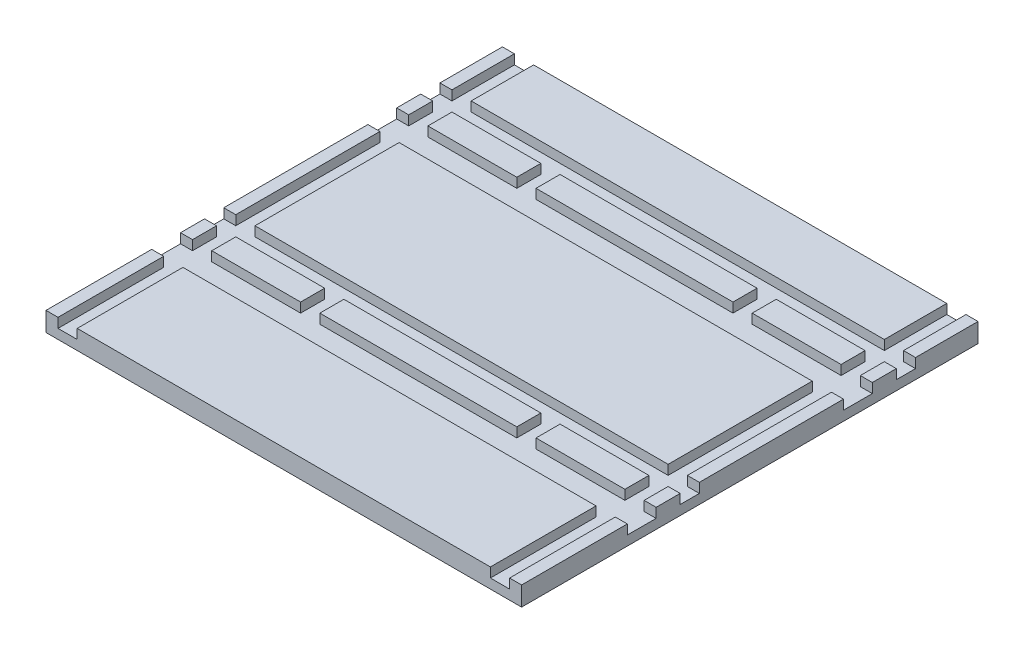
SolidWorks part; units mm, degrees
ref_plane "Front Plane" through (0, 0, 0) normal (0, 0, 1) x (1, 0, 0)
ref_plane "Top Plane" through (0, 0, 0) normal (0, 1, 0) x (1, 0, 0)
ref_plane "Right Plane" through (0, 0, 0) normal (1, 0, 0) x (0, 0, -1)
sketch "Sketch2" plane through (0, 0, 0) normal (0, 1, 0) x (1, 0, 0)
  line L9 (-60.325, -60.325) -> (60.325, -60.325)
  line L10 (-60.325, -60.325) -> (-60.325, 60.325)
  line L11 (-60.325, 60.325) -> (60.325, 60.325)
  line L16 (60.325, -60.325) -> (60.325, 60.325)
  line L17 (-60.325, -60.325) -> (60.325, 60.325) construction
  line L18 (-60.325, 60.325) -> (60.325, -60.325) construction
  point P0 (0, 0)
  dimension "D1" = 120.65
  dimension "D2" = 120.65
extrude "Boss-Extrude1" add sketch "Sketch2" along normal blind 2.54
sketch "Sketch3" plane through (0, 2.54, 0) normal (0, 1, 0) x (1, 0, 0)
  line L0 (57.15, 0) -> (-57.15, 0) construction
  line L5 (-57.15, -57.15) -> (57.15, 57.15) construction
  line L6 (-57.15, 57.15) -> (57.15, -57.15) construction
  line L7 (-57.15, 0) -> (0, 57.15) construction
  line L8 (0, 57.15) -> (0, -57.15) construction
  line L9 (0, -57.15) -> (57.15, 0) construction
  line L10 (57.15, 0) -> (0, 57.15) construction
  line L11 (0, -57.15) -> (-57.15, 0) construction
  line L12 (-60.325, -24.765) -> (-59.69, -24.765)
  line L13 (-60.325, 60.325) -> (-60.325, -60.325) construction
  line L14 (60.325, -60.325) -> (60.325, 60.325) construction
  line L15 (60.325, -32.385) -> (59.69, -32.385)
  line L16 (-28.575, -28.575) -> (28.575, -28.575) construction
  line L17 (-31.115, -24.765) -> (-31.115, -18.415)
  line L18 (-26.035, -24.765) -> (-26.035, -18.415)
  line L19 (-28.575, -28.575) -> (-28.575, 28.575) construction
  line L20 (28.575, 28.575) -> (28.575, -28.575) construction
  line L21 (-57.15, 57.15) -> (-57.15, -57.15) construction
  line L22 (-57.15, -57.15) -> (57.15, -57.15) construction
  line L23 (57.15, -57.15) -> (57.15, 57.15) construction
  line L24 (57.15, 57.15) -> (-57.15, 57.15) construction
  line L25 (-59.69, 60.325) -> (-59.69, 43.815)
  line L26 (60.325, 60.325) -> (-60.325, 60.325) construction
  line L27 (-60.325, -60.325) -> (60.325, -60.325) construction
  line L28 (-54.61, 60.325) -> (-54.61, 43.815)
  line L29 (-60.325, -15.875) -> (60.325, -15.875) construction
  line L30 (-60.325, -18.415) -> (-59.69, -18.415)
  line L31 (60.325, -13.335) -> (59.69, -13.335)
  line L32 (-26.035, -24.765) -> (26.035, -24.765)
  line L33 (-26.035, -18.415) -> (26.035, -18.415)
  line L34 (31.115, -24.765) -> (31.115, -18.415)
  line L35 (26.035, -24.765) -> (26.035, -18.415)
  line L36 (31.115, -24.765) -> (54.61, -24.765)
  line L37 (31.115, -18.415) -> (54.61, -18.415)
  line L38 (-59.69, -13.335) -> (-60.325, -13.335)
  line L39 (-54.61, -18.415) -> (-31.115, -18.415)
  line L40 (-54.61, -24.765) -> (-31.115, -24.765)
  line L41 (-59.69, -32.385) -> (-60.325, -32.385)
  line L42 (59.69, 60.325) -> (59.69, 43.815)
  line L43 (54.61, 60.325) -> (54.61, 43.815)
  line L44 (-54.61, -32.385) -> (-54.61, -60.325)
  line L45 (-54.61, -18.415) -> (-54.61, -24.765)
  line L46 (54.61, -32.385) -> (54.61, -60.325)
  line L47 (59.69, -24.765) -> (60.325, -24.765)
  line L48 (59.69, -18.415) -> (60.325, -18.415)
  line L49 (54.61, -18.415) -> (54.61, -24.765)
  line L50 (54.61, -13.335) -> (-54.61, -13.335)
  line L51 (54.61, -32.385) -> (-54.61, -32.385)
  line L52 (59.69, -32.385) -> (59.69, -60.325)
  line L53 (59.69, -18.415) -> (59.69, -24.765)
  line L54 (-59.69, -18.415) -> (-59.69, -24.765)
  line L55 (-59.69, -32.385) -> (-59.69, -60.325)
  line L56 (60.325, -60.325) -> (59.69, -60.325)
  line L57 (-60.325, -60.325) -> (-60.325, -32.385)
  line L58 (-60.325, 60.325) -> (-59.69, 60.325)
  line L59 (60.325, 60.325) -> (60.325, 43.815)
  line L60 (-59.69, -60.325) -> (-60.325, -60.325)
  line L61 (54.61, -60.325) -> (-54.61, -60.325)
  line L62 (60.325, -32.385) -> (60.325, -60.325)
  line L63 (60.325, -18.415) -> (60.325, -24.765)
  line L64 (-60.325, -13.335) -> (-60.325, 24.765)
  line L65 (-60.325, -24.765) -> (-60.325, -18.415)
  line L66 (-54.61, 32.385) -> (-31.115, 32.385)
  line L67 (54.61, 43.815) -> (-54.61, 43.815)
  line L68 (-26.035, 32.385) -> (26.035, 32.385)
  line L69 (26.035, 32.385) -> (26.035, 38.735)
  line L70 (-26.035, 32.385) -> (-26.035, 38.735)
  line L71 (31.115, 32.385) -> (54.61, 32.385)
  line L72 (-54.61, 38.735) -> (-31.115, 38.735)
  line L73 (-26.035, 38.735) -> (26.035, 38.735)
  line L74 (-54.61, 38.735) -> (-54.61, 32.385)
  line L75 (31.115, 32.385) -> (31.115, 38.735)
  line L76 (54.61, 24.765) -> (-54.61, 24.765)
  line L77 (-31.115, 32.385) -> (-31.115, 38.735)
  line L78 (31.115, 38.735) -> (54.61, 38.735)
  line L79 (54.61, 38.735) -> (54.61, 32.385)
  line L80 (-28.575, 28.575) -> (28.575, 28.575) construction
  line L81 (-54.61, 24.765) -> (-54.61, -13.335)
  line L82 (-54.61, 38.735) -> (-54.61, 32.385)
  line L83 (54.61, 38.735) -> (54.61, 32.385)
  line L84 (54.61, 24.765) -> (54.61, -13.335)
  line L85 (-54.61, 60.325) -> (54.61, 60.325)
  line L86 (59.69, 60.325) -> (60.325, 60.325)
  line L87 (-59.69, 24.765) -> (-60.325, 24.765)
  line L88 (-59.69, 32.385) -> (-60.325, 32.385)
  line L89 (-59.69, 38.735) -> (-60.325, 38.735)
  line L90 (-59.69, 43.815) -> (-60.325, 43.815)
  line L91 (-59.69, 38.735) -> (-59.69, 32.385)
  line L92 (-60.325, 43.815) -> (-60.325, 60.325)
  line L93 (-59.69, 24.765) -> (-59.69, -13.335)
  line L94 (-60.325, 32.385) -> (-60.325, 38.735)
  line L95 (59.69, 43.815) -> (60.325, 43.815)
  line L96 (59.69, 38.735) -> (60.325, 38.735)
  line L97 (59.69, 32.385) -> (60.325, 32.385)
  line L98 (59.69, 24.765) -> (60.325, 24.765)
  line L99 (59.69, 24.765) -> (59.69, -13.335)
  line L100 (60.325, 24.765) -> (60.325, -13.335)
  line L101 (59.69, 38.735) -> (59.69, 32.385)
  line L102 (60.325, 38.735) -> (60.325, 32.385)
  point P0 (0, 0)
  line M17 (60.325, -60.325) -> (60.325, 60.325)
  line M18 (60.325, 60.325) -> (-60.325, 60.325)
  line M19 (-60.325, 60.325) -> (-60.325, -60.325)
  line M20 (-60.325, -60.325) -> (60.325, -60.325)
  dimension "D1" = 114.3
  dimension "D2" = 114.3
  dimension "D3" = 7.62
  dimension "D4" = 3.81
  dimension "D5" = 5.08
  dimension "D6" = 2.54
  dimension "D7" = 2.54
  dimension "D8" = 5.08
  dimension "D9" = 12.7
  dimension "D10" = 2.54
  dimension "D11" = 5.08
extrude "Boss-Extrude2" add sketch "Sketch3" along normal blind 2.54 contours L39 L45 L40 L17 | L32 L35 L33 L18 | L49 L37 L34 L36 | L46 L51 L44 M20 | L93 L87 L38 M19 | L91 L89 L88 M19 | L90 L25 M18 M19 | L42 L95 M17 M18 | L96 L101 L97 M17 | L98 L99 L31 M17 | L54 L12 L65 L30 | L53 L47 L63 L48 | L52 L56 L62 L15 | L55 L60 L57 L41 | L66 L77 L72 L74 | L68 L69 L73 L70 | L71 L79 L78 L75 | L28 L67 L43 L85 | L50 L81 L76 L84
sketch "Sketch5" plane through (60.325, 0, 0) normal (1, 0, 0) x (0, 0, -1)
  line L0 (-60.325, 0) -> (60.325, 0)
  line L1 (60.325, 0) -> (60.325, 5.08)
  line L2 (60.325, 5.08) -> (43.815, 5.08)
  line L3 (43.815, 5.08) -> (43.815, 2.54)
  line L4 (43.815, 2.54) -> (38.735, 2.54)
  line L5 (38.735, 2.54) -> (38.735, 5.08)
  line L6 (38.735, 5.08) -> (32.385, 5.08)
  line L7 (32.385, 5.08) -> (32.385, 2.54)
  line L8 (32.385, 2.54) -> (24.765, 2.54)
  line L9 (24.765, 2.54) -> (24.765, 5.08)
  line L10 (24.765, 5.08) -> (-13.335, 5.08)
  line L11 (-13.335, 5.08) -> (-13.335, 2.54)
  line L12 (-13.335, 2.54) -> (-18.415, 2.54)
  line L13 (-18.415, 2.54) -> (-18.415, 5.08)
  line L14 (-18.415, 5.08) -> (-24.765, 5.08)
  line L15 (-24.765, 5.08) -> (-24.765, 2.54)
  line L16 (-24.765, 2.54) -> (-32.385, 2.54)
  line L17 (-32.385, 2.54) -> (-32.385, 5.08)
  line L18 (-32.385, 5.08) -> (-60.325, 5.08)
  line L19 (-60.325, 5.08) -> (-60.325, 0)
extrude "Boss-Extrude4" add sketch "Sketch5" along normal blind 2.54
mirror "Mirror2" about plane through (0, 0, 0) normal (1, 0, 0) of "Boss-Extrude4"
